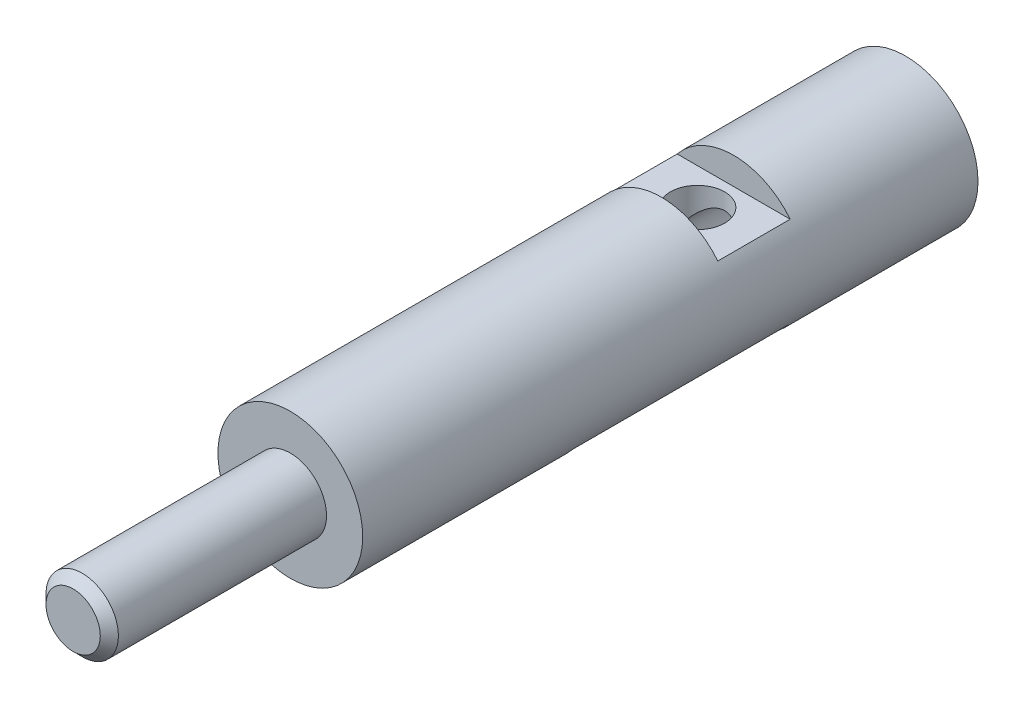
SolidWorks part; units mm, degrees
material "Cast Alloy Steel"
ref_plane "Front Plane" through (0, 0, 0) normal (0, 0, 1) x (1, 0, 0)
ref_plane "Top Plane" through (0, 0, 0) normal (0, 1, 0) x (1, 0, 0)
ref_plane "Right Plane" through (0, 0, 0) normal (1, 0, 0) x (0, 0, -1)
sketch "Sketch1" plane through (0, 0, 0) normal (0, 0, 1) x (1, 0, 0)
  circle A0 centre (0, 0) radius 4
  dimension "D1" = 8
extrude "Boss-Extrude1" add sketch "Sketch1" against normal blind 34
sketch "Sketch2" plane through (0, 0, 0) normal (0, 0, 1) x (1, 0, 0)
  circle A0 centre (0, 0) radius 2
  dimension "D1" = 4
extrude "Boss-Extrude2" add sketch "Sketch2" along normal blind 12
chamfer "Chamfer1" distance 0.5 angle 45 1 edges at (2, 0, 12)
hole_wizard "Ø3.2 (3.2) Diameter Hole1" positions "Sketch3" profile "Sketch4" hole size "Ø3.2" standard "ANSI Metric"
sketch "Sketch3" plane through (0, 0, -34) normal (0, 0, -1) x (-1, 0, 0)
  point P0 (0, 0)
sketch "Sketch4" plane through (0, 0, -34) normal (1, 0, 0) x (0, 1, 0)
  line L0 (0, 0) -> (0, 14.9614)
  line L1 (0, 14.9614) -> (1.6, 14)
  line L2 (1.6, 14) -> (1.6, 0)
  line L5 (1.6, 0) -> (0, 0)
  line L10 (0, 14.9614) -> (-1.6, 14) construction
  line L11 (0, -6.35) -> (0, 107.95) construction
  dimension "Hole Dia." = 3.2
  dimension "Hole Depth" = 14
  dimension "Drill Angle" = 118
sketch "Sketch5" plane through (0, 0, 0) normal (1, 0, 0) x (0, 0, -1)
  line L0 (0, -4) -> (34, -4) construction
  line L1 (24.5, -4) -> (12.5, -4)
  line L2 (24.5, -4) -> (24.5, -2.5)
  line L3 (24.5, -2.5) -> (12.5, -2.5)
  line L4 (12.5, -4) -> (12.5, -2.5)
  line L5 (34, 4) -> (0, 4) construction
  line L6 (24.5, 4) -> (20.5, 4)
  line L7 (24.5, 4) -> (24.5, 2.5)
  line L8 (24.5, 2.5) -> (20.5, 2.5)
  line L9 (20.5, 4) -> (20.5, 2.5)
  line L10 (34, -4) -> (34, 4) construction
  dimension "D1" = 12
  dimension "D2" = 1.5
  dimension "D3" = 1.5
  dimension "D4" = 4
  dimension "D5" = 9.5
extrude "Cut-Extrude1" cut sketch "Sketch5" against normal through all both and the other way through all
hole_wizard "Ø3.0 (3) Diameter Hole1" positions "Sketch6" profile "Sketch7" hole size "Ø3.0" standard "ANSI Metric"
sketch "Sketch6" plane through (0, 2.5, 0) normal (0, 1, 0) x (1, 0, 0)
  line L0 (-3.1225, 20.5) -> (3.1225, 24.5) construction
  point P7 (0, 22.5)
sketch "Sketch7" plane through (0, 2.5, -22.5) normal (1, 0, 0) x (0, 0, 1)
  line L0 (0, 0) -> (0, 0.9)
  line L1 (0, 0.9) -> (1.5, 0.9)
  line L2 (1.5, 0.9) -> (1.5, 0)
  line L5 (1.5, 0) -> (0, 0)
  line L11 (0, -6.35) -> (0, 107.95) construction
  dimension "Thru Hole Dia." = 3
  dimension "Thru Hole Depth" = 0.9
